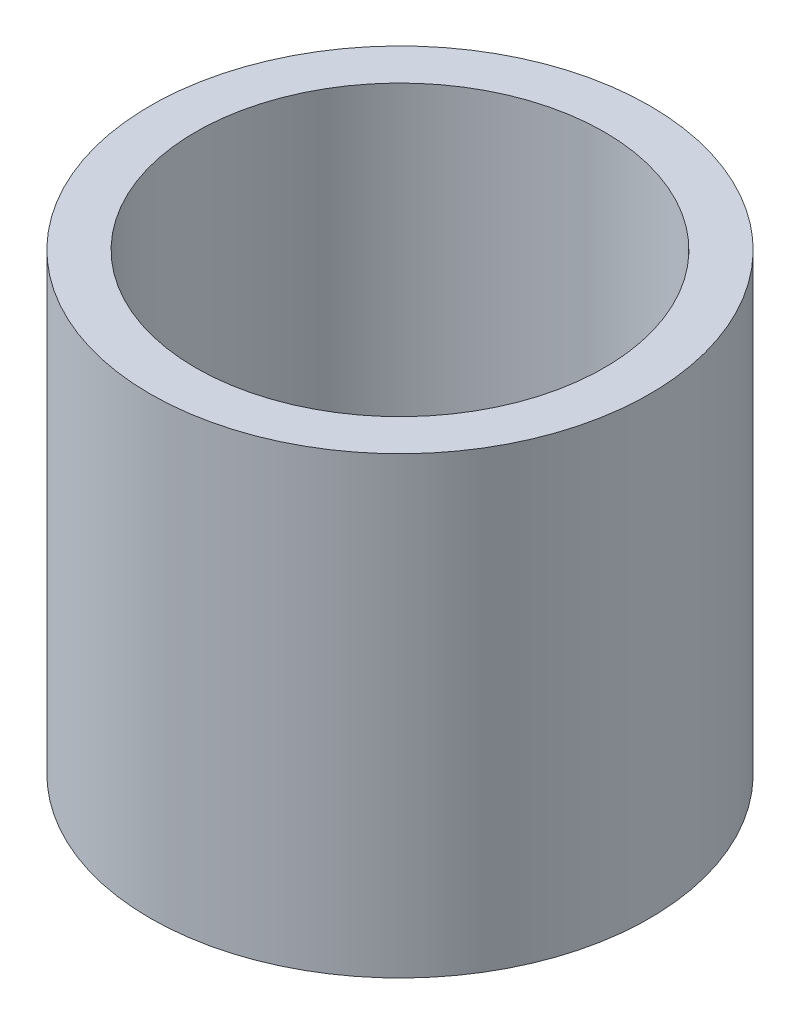
SolidWorks part; units mm, degrees
ref_plane "Front Plane" through (0, 0, 0) normal (0, 0, 1) x (1, 0, 0)
ref_plane "Top Plane" through (0, 0, 0) normal (0, 1, 0) x (1, 0, 0)
ref_plane "Right Plane" through (0, 0, 0) normal (1, 0, 0) x (0, 0, -1)
sketch "Esquisse2" plane through (0, 0, 0) normal (0, 1, 0) x (1, 0, 0)
  circle A0 centre (0, 0) radius 2.25
  circle A1 centre (0, 0) radius 2.75
  dimension "D1" = 4.5
  dimension "D2" = 5.5
extrude "Boss.-Extru.2" add sketch "Esquisse2" along normal blind 5
